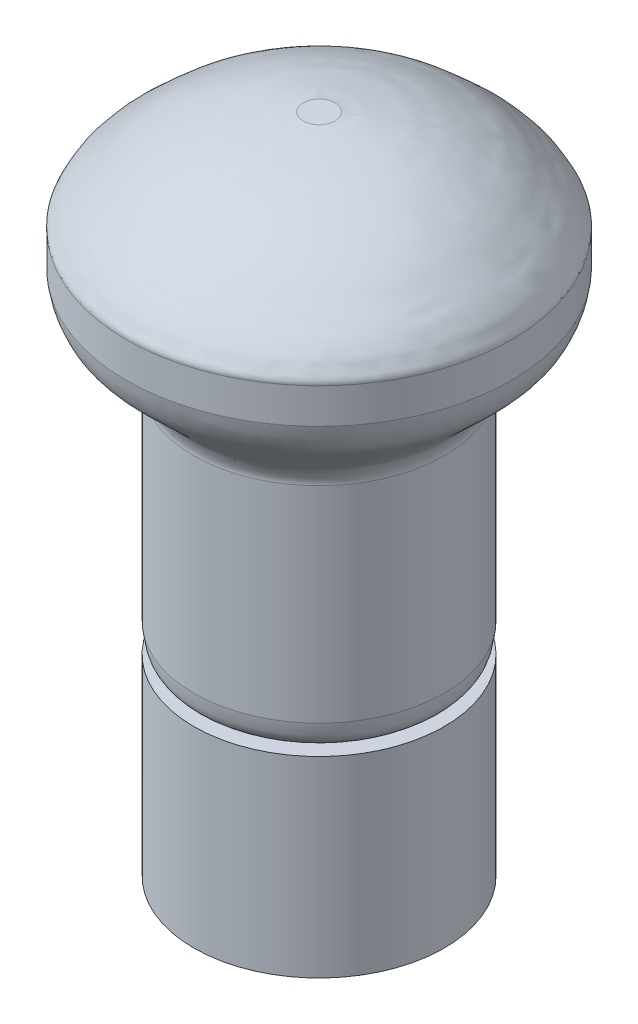
SolidWorks part; units mm, degrees
ref_plane "Front Plane" through (0, 0, 0) normal (0, 0, 1) x (1, 0, 0)
ref_plane "Top Plane" through (0, 0, 0) normal (0, 1, 0) x (1, 0, 0)
ref_plane "Right Plane" through (0, 0, 0) normal (1, 0, 0) x (0, 0, -1)
sketch "Sketch1" plane through (0, 0, 0) normal (1, 0, 0) x (0, 0, -1)
  line L0 (26.0878, 274.978) -> (26.0878, 232.1195)
  line L2 (40.135, 299.274) -> (-40.135, 299.274) construction
  line L5 (0, 324) -> (3.2968, 324)
  line L8 (0, 324) -> (0, 0) construction
  line L9 (26.0878, 262.3641) -> (26.0878, 259.4973) construction
  line L12 (40.135, 302.9291) -> (40.135, 295.6188)
  line L16 (0, 0) -> (51.9362, 327.9125) construction
  line L17 (0, 324) -> (0, 332) construction
  line L18 (26.0878, 274.978) -> (26.0878, 268.978) construction
  line L19 (26.0878, 268.978) -> (26.0878, 248.978) construction
  line L20 (26.0878, 268.978) -> (42.6019, 268.978) construction
  line L21 (26.0878, 274.978) -> (43.5522, 274.978) construction
  line L22 (26.0878, 248.978) -> (39.4342, 248.978) construction
  line L23 (0, 0) -> (-51.9362, 327.9125) construction
  line L24 (-47.4003, 299.274) -> (-47.4003, 268.978) construction
  line L25 (-47.4003, 268.978) -> (-42.6019, 268.978) construction
  line L26 (0, 332) -> (0, 76.96) construction
  line L27 (0, 76.96) -> (400, 76.96) construction
  line L28 (0, 76.96) -> (-400, 76.96) construction
  line L29 (-200, 76.96) -> (-200, 183.96) construction
  line L30 (200, 76.96) -> (200, 183.96) construction
  line L31 (-200, 183.96) -> (-200, 182.57) construction
  line L32 (-200, 182.57) -> (400, 182.57) construction
  line L33 (-200, 182.57) -> (-400, 182.57) construction
  line L38 (0, 186.1152) -> (0, 324)
  line L39 (26.0878, 232.1195) -> (26.0878, 182.57) construction
  line L41 (21.6442, 226.0993) -> (26.0878, 226.0993)
  line L42 (26.0878, 226.0993) -> (26.0878, 186.1152)
  line L43 (26.0878, 186.1152) -> (0, 186.1152)
  arc A0 (-298.7691, 144.7791) -> (305.6579, 129.6043) centre (0, 0) cw construction
  spline S0 degree 3 poles (21.6442, 226.0993) (21.9584, 226.1509) (22.4049, 226.153) (22.896, 226.3321) (23.44, 226.7494) (24.2443, 227.2014) (25.0066, 227.9724) (25.5796, 228.9522) (25.8622, 230.393) (26.0228, 231.4436) (26.0878, 232.1195) knots 0 0 0 0 0.091924 0.112491 0.205673 0.333714 0.459267 0.602423 0.748839 1 1 1 1
  spline S1 degree 3 poles (3.2968, 324) (4.1972, 323.8396) (5.699, 323.816) (7.6935, 323.4297) (9.2722, 323.1563) (10.7507, 322.8538) (12.1816, 322.5577) (13.6372, 322.313) (14.8643, 321.9117) (15.9115, 321.5662) (16.81, 321.2491) (17.7339, 321.0149) (18.8379, 320.6416) (19.931, 320.1935) (21.0686, 319.6948) (22.141, 319.2627) (23.2156, 318.6856) (24.4371, 318.1163) (25.6762, 317.3518) (27.1066, 316.7518) (28.4318, 315.7832) (29.7322, 314.8939) (31.058, 313.93) (32.1959, 312.8581) (33.3378, 311.8503) (34.4539, 310.9646) (35.3895, 309.8867) (36.5078, 309.0949) (37.2942, 308.0208) (38.1233, 307.1238) (38.9048, 306.0961) (39.4724, 304.6349) (40.2774, 303.734) (40.135, 302.9291) knots 0 0 0 0 0.061585 0.100795 0.136831 0.1697 0.202569 0.235438 0.269088 0.289473 0.309858 0.333319 0.353706 0.388423 0.412965 0.437514 0.46634 0.495168 0.528354 0.564387 0.59925 0.638593 0.670824 0.709635 0.743897 0.773612 0.805519 0.839783 0.864953 0.89467 0.922395 0.951224 1 1 1 1
  spline S2 degree 3 poles (40.135, 295.6188) (39.9636, 294.7131) (39.7869, 293.3689) (39.1095, 291.6901) (38.6019, 290.4599) (37.8418, 289.2392) (36.9195, 288.2279) (35.9232, 287.2651) (34.974, 286.2515) (33.8311, 285.3463) (32.8233, 284.2966) (31.8701, 283.2868) (30.7668, 282.4387) (29.8742, 281.4644) (28.8604, 280.5152) (28.0567, 279.5119) (27.1438, 278.5569) (26.4968, 277.0287) (26.0081, 275.8567) (26.0878, 274.978) knots 0 0 0 0 0.108356 0.15601 0.210945 0.263562 0.322855 0.370186 0.4254 0.484692 0.539909 0.595126 0.646549 0.701764 0.749093 0.808384 0.85195 0.901837 1 1 1 1
  point P10 (0, 299.274)
  point P63 (0, 299.274)
  dimension "D3" = 9
  dimension "D1" = 40.135
  dimension "D4" = 8
  dimension "D9" = 6
  dimension "D10" = 20
  dimension "D13" = 255.04
  dimension "D14" = 107
  dimension "D15" = 107
  dimension "D16" = 332
  dimension "D17" = 105.61
  dimension "D18" = 105.61
revolve "Revolve5" add sketch "Sketch1" angle 360 about L8
